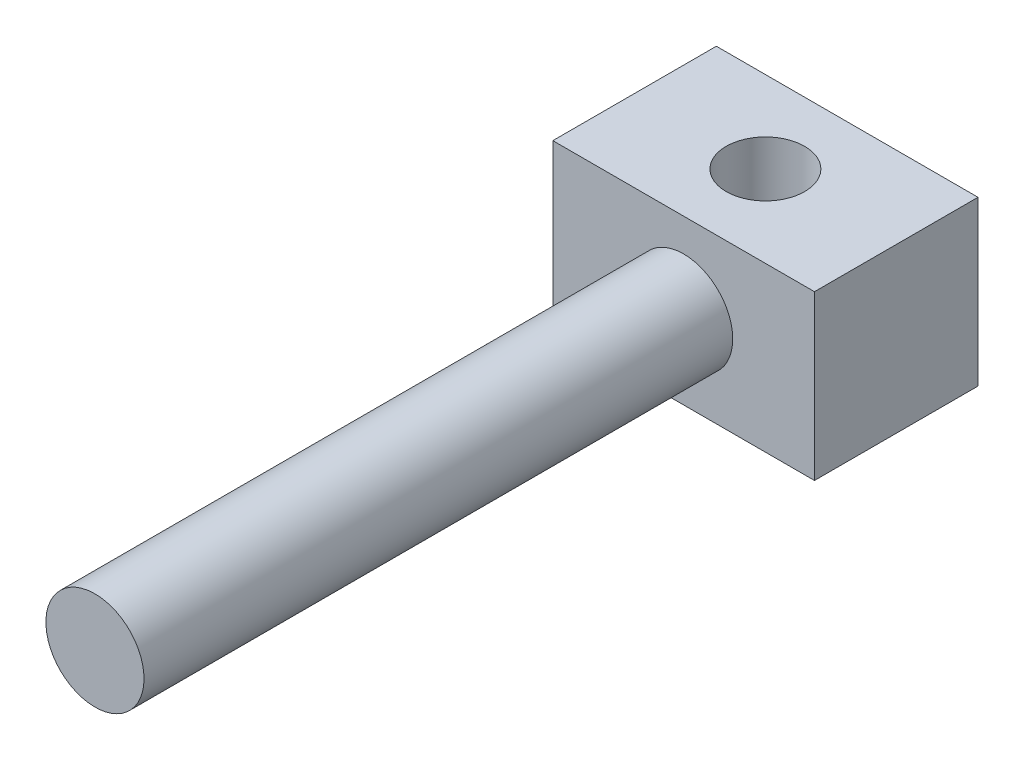
SolidWorks part; units mm, degrees
ref_plane "Front Plane" through (0, 0, 0) normal (0, 0, 1) x (1, 0, 0)
ref_plane "Top Plane" through (0, 0, 0) normal (0, 1, 0) x (1, 0, 0)
ref_plane "Right Plane" through (0, 0, 0) normal (1, 0, 0) x (0, 0, -1)
sketch "Sketch1" plane through (0, 0, 0) normal (0, 1, 0) x (1, 0, 0)
  line L2 (-4, -2.5) -> (-4, 2.5)
  line L3 (-4, 2.5) -> (4, 2.5)
  line L4 (4, 2.5) -> (4, -2.5)
  line L22 (0, 2.5) -> (0, -2.5) construction
  line L23 (-4, -2.5) -> (4, -2.5)
  point P6 (0, 0)
  dimension "D1" = 5
  dimension "D2" = 8
extrude "Boss-Extrude1" add sketch "Sketch1" along normal mid plane 5
sketch "Sketch2" plane through (0, 0, 0) normal (0, 1, 0) x (1, 0, 0)
  line L0 (-1.5, -2.5) -> (1.5, -2.5)
  line L1 (-1.5, -2.5) -> (-1.5, -5.5)
  line L2 (-1.5, -5.5) -> (1.5, -5.5)
  line L3 (1.5, -2.5) -> (1.5, -5.5)
  line L4 (-4, -2.5) -> (4, -2.5) construction
  dimension "D1" = 3
  dimension "D2" = 3
extrude "Boss-Extrude2" add sketch "Sketch2" along normal mid plane 3
sketch "Sketch3" plane through (0, 0, 5.5) normal (0, 0, 1) x (1, 0, 0)
  line L4 (-1.5, -1.5) -> (1.5, -1.5)
  line L5 (1.5, -1.5) -> (1.5, 1.5)
  line L6 (1.5, 1.5) -> (-1.5, 1.5)
  line L7 (-1.5, 1.5) -> (-1.5, -1.5)
  line L8 (-1.5, -1.5) -> (1.5, -1.5)
  line L9 (1.5, -1.5) -> (1.5, 1.5)
  line L10 (1.5, 1.5) -> (-1.5, 1.5)
  line L11 (-1.5, 1.5) -> (-1.5, -1.5)
  circle A0 centre (0, 0) radius 1.5
  line M6 (-1.5, -1.5) -> (1.5, -1.5)
  line M7 (1.5, -1.5) -> (1.5, 1.5)
  line M8 (1.5, 1.5) -> (-1.5, 1.5)
  line M9 (-1.5, 1.5) -> (-1.5, -1.5)
  dimension "D1" = 0
extrude "Cut-Extrude2" cut sketch "Sketch3" against normal up to surface (3 mm away) contours A0 L10 M9 | A0 L9 M8 | A0 L8 M7 | A0 L11 M6 up to face at (0, 0, 2.5)
sketch "Sketch5" plane through (0, 2.5, 0) normal (0, 1, 0) x (1, 0, 0)
  circle A0 centre (0, 0) radius 1.2
extrude "Cut-Extrude3" cut sketch "Sketch5" against normal through all
sketch "Sketch6" plane through (0, 0, 5.5) normal (0, 0, 1) x (1, 0, 0)
  circle A1 centre (0, 0) radius 1.5
  circle A2 centre (0, 0) radius 1.5
  dimension "D1" = 0
extrude "Boss-Extrude3" add sketch "Sketch6" along normal blind 15
